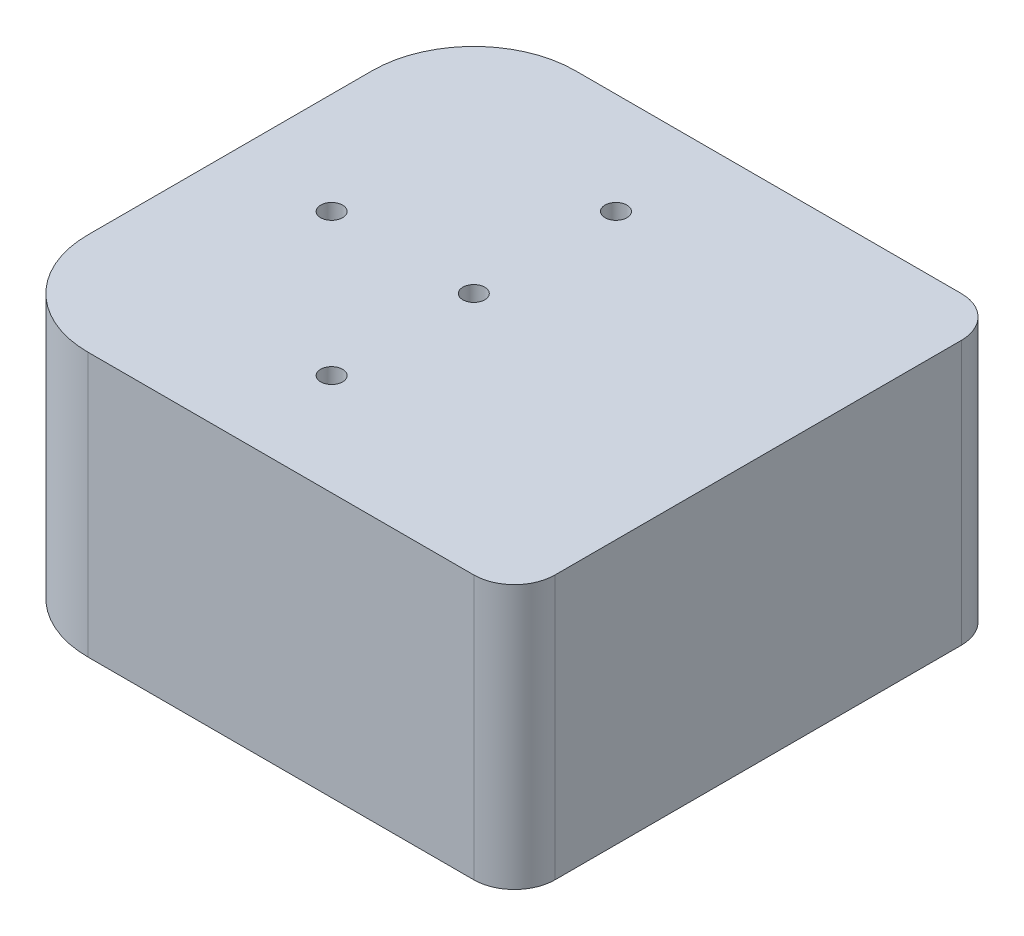
SolidWorks part; units mm, degrees
ref_plane "Front Plane" through (0, 0, 0) normal (0, 0, 1) x (1, 0, 0)
ref_plane "Top Plane" through (0, 0, 0) normal (0, 1, 0) x (1, 0, 0)
ref_plane "Right Plane" through (0, 0, 0) normal (1, 0, 0) x (0, 0, -1)
sketch "Sketch1" plane through (0, 0, 0) normal (0, 1, 0) x (1, 0, 0)
  line L0 (0, 7) -> (0, 0) construction
  line L1 (0, 0) -> (0, -7) construction
  line L2 (0, 0) -> (-7, 0) construction
  line L4 (-7, 12) -> (12, 12)
  line L5 (-12, 7) -> (-12, -7)
  line L6 (-7, -12) -> (12, -12)
  line L7 (14, 10) -> (14, -10)
  circle A0 centre (0, 0) radius 0.54
  circle A1 centre (-7, 0) radius 0.54
  circle A2 centre (0, 7) radius 0.54
  circle A3 centre (0, -7) radius 0.54
  arc A4 (-7, -12) -> (-12, -7) centre (-7, -7) cw
  arc A5 (-12, 7) -> (-7, 12) centre (-7, 7) cw
  arc A6 (12, -12) -> (14, -10) centre (12, -10) ccw
  arc A7 (12, 12) -> (14, 10) centre (12, 10) cw
  dimension "D1" = 1.08
  dimension "D7" = 5
  dimension "D8" = 2
  dimension "D2" = 7
  dimension "D3" = 14
  dimension "D4" = 5
  dimension "D5" = 5
  dimension "D6" = 5
extrude "Boss-Extrude1" add sketch "Sketch1" along normal blind 13
